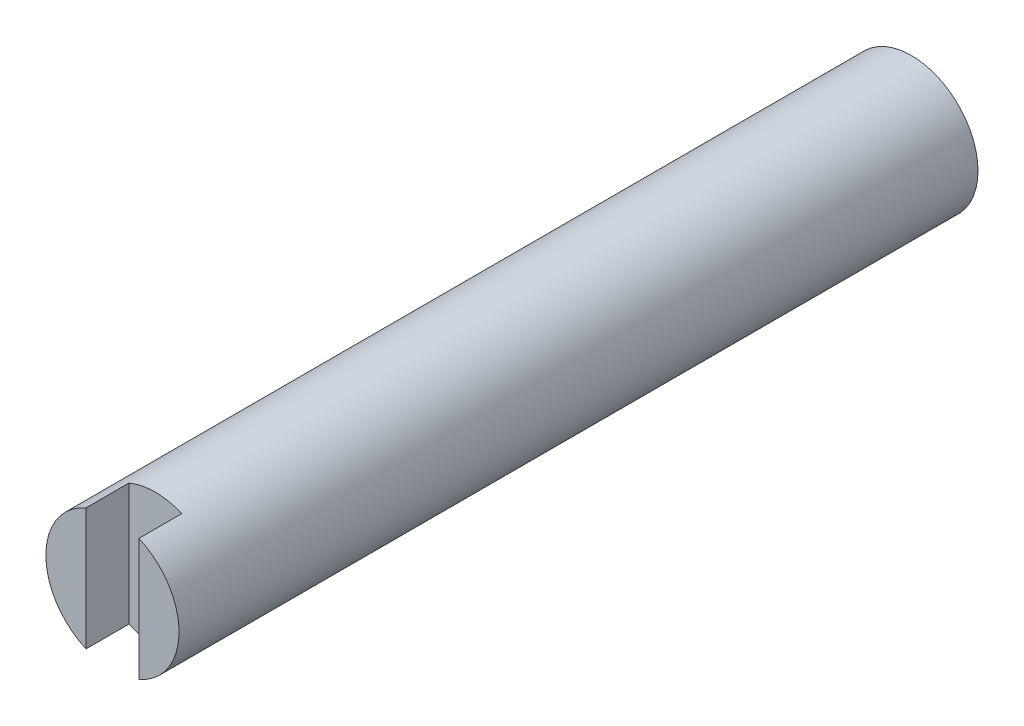
SolidWorks part; units mm, degrees
ref_plane "Спереди" through (0, 0, 0) normal (0, 0, 1) x (1, 0, 0)
ref_plane "Сверху" through (0, 0, 0) normal (0, 1, 0) x (1, 0, 0)
ref_plane "Справа" through (0, 0, 0) normal (1, 0, 0) x (0, 0, -1)
sketch "Эскиз1" plane through (0, 0, 0) normal (0, 0, 1) x (1, 0, 0)
  circle A0 centre (0, 0) radius 12.5
extrude "Вытянуть1" add sketch "Эскиз1" along normal blind 150 from offset 10
sketch "Эскиз2" plane through (0, 0, 0) normal (0, 1, 0) x (1, 0, 0)
  line L1 (-4.9685, -151.9621) -> (4.9656, -151.9621)
  line L2 (-4.9685, -151.9621) -> (-4.9685, -188.4338)
  line L3 (-4.9685, -188.4338) -> (4.9656, -188.4338)
  line L4 (4.9656, -151.9621) -> (4.9656, -188.4338)
extrude "Вырез-Вытянуть1" cut sketch "Эскиз2" against normal mid plane 70
sketch "Эскиз3" plane through (0, 0, 0) normal (1, 0, 0) x (0, 0, -1)
  circle A0 centre (-148.9416, 0) radius 5
